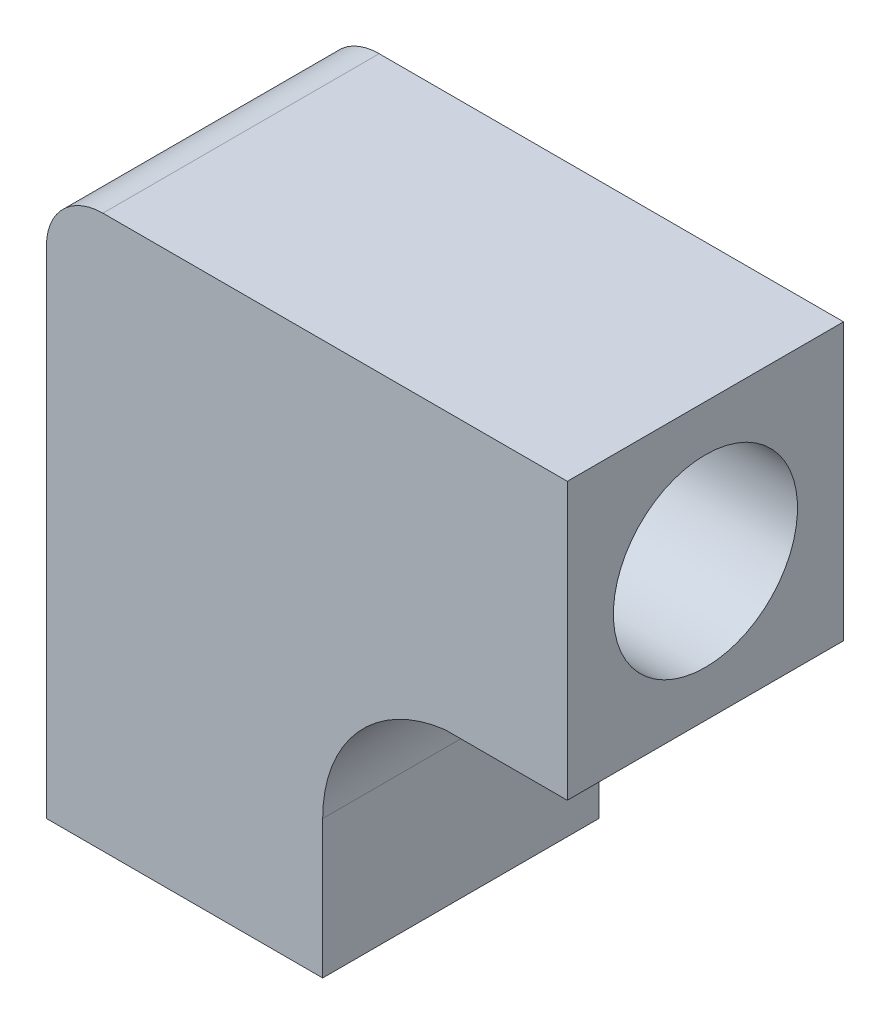
SolidWorks part; units mm, degrees
ref_plane "Front Plane" through (0, 0, 0) normal (0, 0, 1) x (1, 0, 0)
ref_plane "Top Plane" through (0, 0, 0) normal (0, 1, 0) x (1, 0, 0)
ref_plane "Right Plane" through (0, 0, 0) normal (1, 0, 0) x (0, 0, -1)
sketch "Sketch1" plane through (0, 0, 0) normal (0, 0, 1) x (1, 0, 0)
  line L0 (0, 0) -> (-6, 0)
  line L1 (-6, 0) -> (-6, 10.7732)
  line L2 (-4.7732, 12) -> (5.3138, 12)
  line L3 (5.3138, 12) -> (5.3138, 6)
  line L4 (5.3138, 6) -> (2.6569, 6)
  line L5 (0, 3) -> (0, 0)
  line L6 (0, 0) -> (0, 3)
  line L7 (5.3138, 12) -> (-4.7732, 12)
  arc A0 (0, 3) -> (2.6569, 6) centre (3.0222, 3) cw
  arc A1 (-4.7732, 12) -> (-6, 10.7732) centre (-4.7732, 10.7732) ccw
  dimension "D2" = 6
  dimension "D3" = 6
extrude "Boss-Extrude2" add sketch "Sketch1" along normal blind 6 contours L2 A1 L1 L0 L5 A0 L4 L3
sketch "Sketch5" plane through (5.3138, 0, 0) normal (1, 0, 0) x (0, 0, -1)
  line L0 (-6, 6) -> (0, 12)
  circle A0 centre (-3, 9) radius 2
  dimension "D1" = 4
sketch "Sketch6" plane through (0, 0, 0) normal (0, -1, 0) x (1, 0, 0)
  line L0 (-6, 0) -> (0, 6)
  circle A0 centre (-3, 3) radius 2
  dimension "D1" = 4
extrude "Cut-Extrude6" cut sketch "Sketch5" against normal blind 6 contours L0 A0 | L0 A0
extrude "Cut-Extrude7" cut sketch "Sketch6" against normal blind 6 contours L0 A0 | L0 A0
